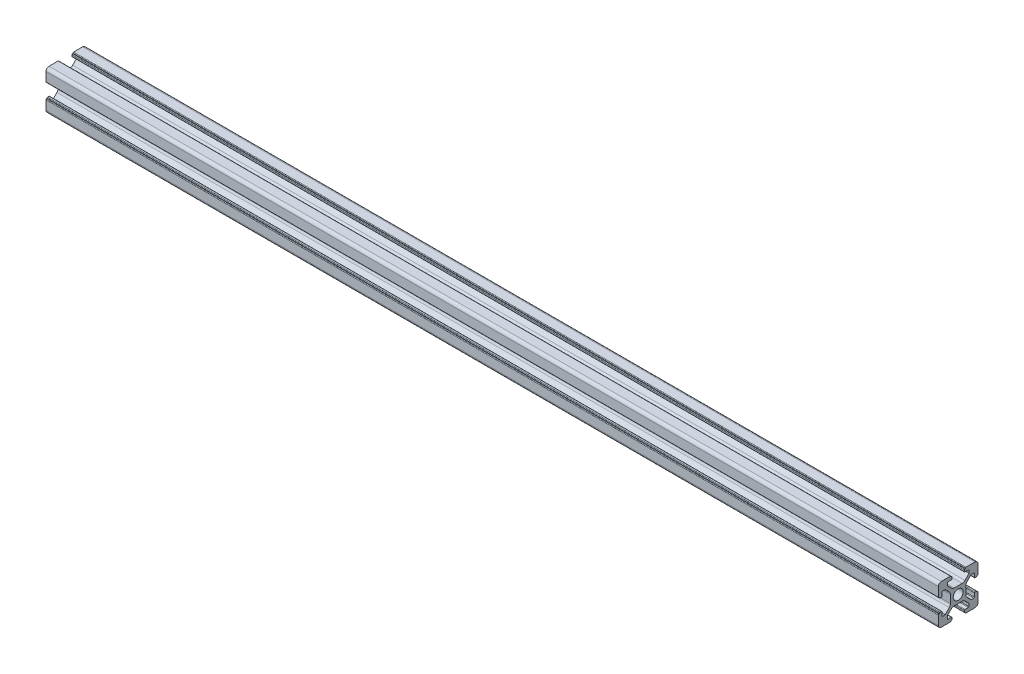
SolidWorks part; units mm, degrees
ref_plane "前视基准面" through (0, 0, 0) normal (0, 0, 1) x (1, 0, 0)
ref_plane "上视基准面" through (0, 0, 0) normal (0, 1, 0) x (1, 0, 0)
ref_plane "右视基准面" through (0, 0, 0) normal (1, 0, 0) x (0, 0, -1)
sketch "草图1" plane through (0, 0, 0) normal (0, 0, 1) x (1, 0, 0)
  line L0 (-186.2583, 66.3079) -> (263.7417, 66.3079)
  dimension "D1" = 450
other "20 2020(1)"
ref_plane "基准面4" through (-186.2583, 66.3079, 0) normal (1, 0, 0) x (0, 1, 0)
sketch "草图11" plane through (-186.2583, 66.3079, 0) normal (1, 0, 0) x (0, 1, 0)
  line L0 (3.9, 0) -> (3.9, -2.0109)
  line L1 (4.4858, -3.4251) -> (6.5607, -5.5)
  line L2 (6.5607, -5.5) -> (7.9, -5.5)
  line L3 (8.2, -5.2) -> (8.2, -3.4)
  line L4 (8.5, -3.1) -> (9.2, -3.1)
  line L5 (9.5, -3.4) -> (9.5, -3.6)
  line L6 (9.5, -3.6) -> (9.7, -3.6)
  line L7 (10, -3.9) -> (10, -8.5)
  line L8 (8.5, -10) -> (3.9, -10)
  line L9 (3.1, -9.2) -> (3.1, -8.5)
  line L10 (3.4, -8.2) -> (5.2, -8.2)
  line L11 (5.5, -7.9) -> (5.5, -6.6849)
  line L12 (5.4121, -6.4728) -> (3.4251, -4.4858)
  line L13 (2.0109, -3.9) -> (0, -3.9)
  line L14 (0, -3.9) -> (-2.0109, -3.9)
  line L15 (-3.4251, -4.4858) -> (-5.4121, -6.4728)
  line L16 (-5.5, -6.6849) -> (-5.5, -7.9)
  line L17 (-5.2, -8.2) -> (-3.4, -8.2)
  line L18 (-3.1, -8.5) -> (-3.1, -9.2)
  line L19 (-3.9, -10) -> (-8.5, -10)
  line L20 (-10, -8.5) -> (-10, -3.9)
  line L21 (-9.7, -3.6) -> (-9.5, -3.6)
  line L22 (-9.5, -3.6) -> (-9.5, -3.4)
  line L23 (-9.2, -3.1) -> (-8.5, -3.1)
  line L24 (-8.2, -3.4) -> (-8.2, -5.2)
  line L25 (-7.9, -5.5) -> (-6.6849, -5.5)
  line L26 (-6.4728, -5.4121) -> (-4.4858, -3.4251)
  line L27 (-3.9, -2.0109) -> (-3.9, 0)
  line L28 (-3.9, 0) -> (-3.9, 2.0109)
  line L29 (-4.4858, 3.4251) -> (-6.4728, 5.4121)
  line L30 (-6.6849, 5.5) -> (-7.9, 5.5)
  line L31 (-8.2, 5.2) -> (-8.2, 3.4)
  line L32 (-8.5, 3.1) -> (-9.2, 3.1)
  line L33 (-9.5, 3.4) -> (-9.5, 3.6)
  line L34 (-9.5, 3.6) -> (-9.7, 3.6)
  line L35 (-10, 3.9) -> (-10, 8.5)
  line L36 (-8.5, 10) -> (-3.9, 10)
  line L37 (-3.6, 9.7) -> (-3.6, 9.5)
  line L38 (-3.6, 9.5) -> (-3.4, 9.5)
  line L39 (-3.1, 9.2) -> (-3.1, 8.5)
  line L40 (-3.4, 8.2) -> (-5.2, 8.2)
  line L41 (-5.5, 7.9) -> (-5.5, 6.6849)
  line L42 (-5.4121, 6.4728) -> (-3.4251, 4.4858)
  line L43 (-2.0109, 3.9) -> (0, 3.9)
  line L44 (0, 3.9) -> (2.0109, 3.9)
  line L45 (3.4251, 4.4858) -> (5.4121, 6.4728)
  line L46 (5.5, 6.6849) -> (5.5, 7.9)
  line L47 (5.2, 8.2) -> (3.4, 8.2)
  line L48 (3.1, 8.5) -> (3.1, 9.2)
  line L49 (3.4, 9.5) -> (3.6, 9.5)
  line L50 (3.6, 9.5) -> (3.6, 9.7)
  line L51 (3.9, 10) -> (8.5, 10)
  line L52 (10, 8.5) -> (10, 3.9)
  line L53 (9.7, 3.6) -> (9.5, 3.6)
  line L54 (9.5, 3.6) -> (9.5, 3.4)
  line L55 (9.2, 3.1) -> (8.5, 3.1)
  line L56 (8.2, 3.4) -> (8.2, 5.2)
  line L57 (7.9, 5.5) -> (6.6849, 5.5)
  line L58 (6.4728, 5.4121) -> (4.4858, 3.4251)
  line L59 (3.9, 2.0109) -> (3.9, 0)
  circle A0 centre (0, 0) radius 2.5
  arc A1 (3.9, -2.0109) -> (4.4858, -3.4251) centre (5.9, -2.0109) ccw
  arc A2 (7.9, -5.5) -> (8.2, -5.2) centre (7.9, -5.2) ccw
  arc A3 (8.5, -3.1) -> (8.2, -3.4) centre (8.5, -3.4) ccw
  arc A4 (9.5, -3.4) -> (9.2, -3.1) centre (9.2, -3.4) ccw
  arc A5 (10, -3.9) -> (9.7, -3.6) centre (9.7, -3.9) ccw
  arc A6 (8.5, -10) -> (10, -8.5) centre (8.5, -8.5) ccw
  arc A7 (3.6, -9.7) -> (3.9, -10) centre (3.9, -9.7) ccw
  arc A8 (3.6, -9.7) -> (3.4, -9.5) centre (3.4, -9.7) ccw
  arc A9 (3.1, -9.2) -> (3.4, -9.5) centre (3.4, -9.2) ccw
  arc A10 (3.4, -8.2) -> (3.1, -8.5) centre (3.4, -8.5) ccw
  arc A11 (5.2, -8.2) -> (5.5, -7.9) centre (5.2, -7.9) ccw
  arc A12 (5.5, -6.6849) -> (5.4121, -6.4728) centre (5.2, -6.6849) ccw
  arc A13 (3.4251, -4.4858) -> (2.0109, -3.9) centre (2.0109, -5.9) ccw
  arc A14 (-2.0109, -3.9) -> (-3.4251, -4.4858) centre (-2.0109, -5.9) ccw
  arc A15 (-5.4121, -6.4728) -> (-5.5, -6.6849) centre (-5.2, -6.6849) ccw
  arc A16 (-5.5, -7.9) -> (-5.2, -8.2) centre (-5.2, -7.9) ccw
  arc A17 (-3.1, -8.5) -> (-3.4, -8.2) centre (-3.4, -8.5) ccw
  arc A18 (-3.4, -9.5) -> (-3.1, -9.2) centre (-3.4, -9.2) ccw
  arc A19 (-3.4, -9.5) -> (-3.6, -9.7) centre (-3.4, -9.7) ccw
  arc A20 (-3.9, -10) -> (-3.6, -9.7) centre (-3.9, -9.7) ccw
  arc A21 (-10, -8.5) -> (-8.5, -10) centre (-8.5, -8.5) ccw
  arc A22 (-9.7, -3.6) -> (-10, -3.9) centre (-9.7, -3.9) ccw
  arc A23 (-9.2, -3.1) -> (-9.5, -3.4) centre (-9.2, -3.4) ccw
  arc A24 (-8.2, -3.4) -> (-8.5, -3.1) centre (-8.5, -3.4) ccw
  arc A25 (-8.2, -5.2) -> (-7.9, -5.5) centre (-7.9, -5.2) ccw
  arc A26 (-6.6849, -5.5) -> (-6.4728, -5.4121) centre (-6.6849, -5.2) ccw
  arc A27 (-4.4858, -3.4251) -> (-3.9, -2.0109) centre (-5.9, -2.0109) ccw
  arc A28 (-3.9, 2.0109) -> (-4.4858, 3.4251) centre (-5.9, 2.0109) ccw
  arc A29 (-6.4728, 5.4121) -> (-6.6849, 5.5) centre (-6.6849, 5.2) ccw
  arc A30 (-7.9, 5.5) -> (-8.2, 5.2) centre (-7.9, 5.2) ccw
  arc A31 (-8.5, 3.1) -> (-8.2, 3.4) centre (-8.5, 3.4) ccw
  arc A32 (-9.5, 3.4) -> (-9.2, 3.1) centre (-9.2, 3.4) ccw
  arc A33 (-10, 3.9) -> (-9.7, 3.6) centre (-9.7, 3.9) ccw
  arc A34 (-8.5, 10) -> (-10, 8.5) centre (-8.5, 8.5) ccw
  arc A35 (-3.6, 9.7) -> (-3.9, 10) centre (-3.9, 9.7) ccw
  arc A36 (-3.1, 9.2) -> (-3.4, 9.5) centre (-3.4, 9.2) ccw
  arc A37 (-3.4, 8.2) -> (-3.1, 8.5) centre (-3.4, 8.5) ccw
  arc A38 (-5.2, 8.2) -> (-5.5, 7.9) centre (-5.2, 7.9) ccw
  arc A39 (-5.5, 6.6849) -> (-5.4121, 6.4728) centre (-5.2, 6.6849) ccw
  arc A40 (-3.4251, 4.4858) -> (-2.0109, 3.9) centre (-2.0109, 5.9) ccw
  arc A41 (2.0109, 3.9) -> (3.4251, 4.4858) centre (2.0109, 5.9) ccw
  arc A42 (5.4121, 6.4728) -> (5.5, 6.6849) centre (5.2, 6.6849) ccw
  arc A43 (5.5, 7.9) -> (5.2, 8.2) centre (5.2, 7.9) ccw
  arc A44 (3.1, 8.5) -> (3.4, 8.2) centre (3.4, 8.5) ccw
  arc A45 (3.4, 9.5) -> (3.1, 9.2) centre (3.4, 9.2) ccw
  arc A46 (3.9, 10) -> (3.6, 9.7) centre (3.9, 9.7) ccw
  arc A47 (10, 8.5) -> (8.5, 10) centre (8.5, 8.5) ccw
  arc A48 (9.7, 3.6) -> (10, 3.9) centre (9.7, 3.9) ccw
  arc A49 (9.2, 3.1) -> (9.5, 3.4) centre (9.2, 3.4) ccw
  arc A50 (8.2, 3.4) -> (8.5, 3.1) centre (8.5, 3.4) ccw
  arc A51 (8.2, 5.2) -> (7.9, 5.5) centre (7.9, 5.2) ccw
  arc A52 (6.6849, 5.5) -> (6.4728, 5.4121) centre (6.6849, 5.2) ccw
  arc A53 (4.4858, 3.4251) -> (3.9, 2.0109) centre (5.9, 2.0109) ccw
  point P0 (0, 0)
